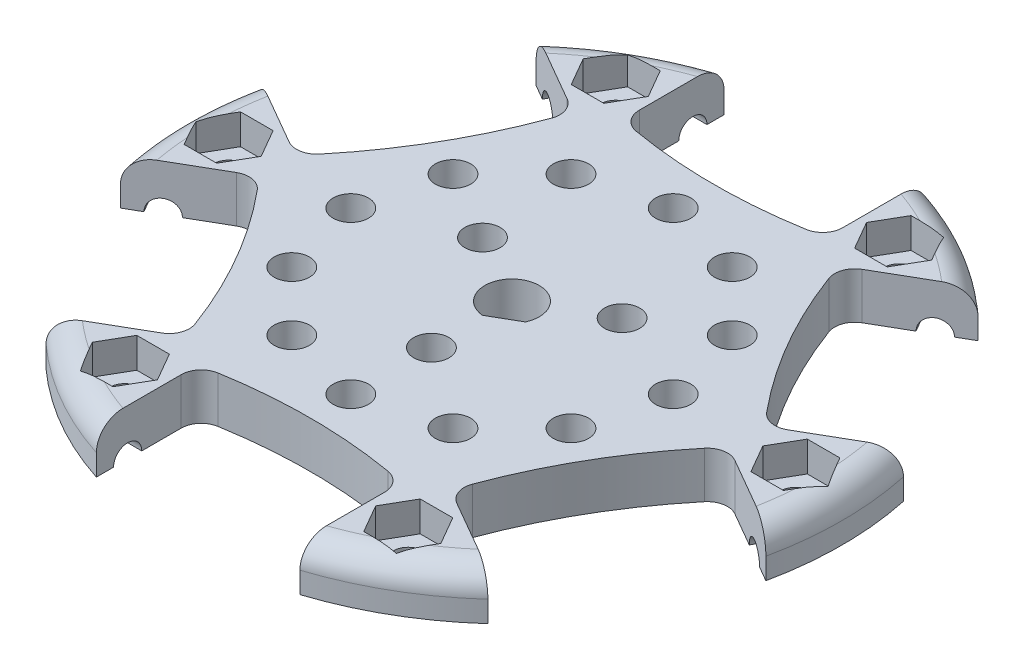
SolidWorks part; units mm, degrees
ref_plane "Plano frontal" through (0, 0, 0) normal (0, 0, 1) x (1, 0, 0)
ref_plane "Plano superior" through (0, 0, 0) normal (0, 1, 0) x (1, 0, 0)
ref_plane "Plano direito" through (0, 0, 0) normal (1, 0, 0) x (0, 0, -1)
sketch "Esboço1" plane through (0, 0, 0) normal (0, 0, 1) x (1, 0, 0)
  line L1 (-32.75, 2.1) -> (-32.75, 0)
  line L2 (-30.25, 4.6) -> (-6.07, 4.6)
  line L15 (-6.07, 4.6) -> (0, 4.6)
  line L17 (0, 0) -> (0, 4.6)
  line L18 (-32.75, 0) -> (0, 0)
  arc A3 (-30.25, 4.6) -> (-32.75, 2.1) centre (-30.25, 2.1) ccw
revolve "Revolução3" add sketch "Esboço1" angle 360 about L17
sketch "Esboço3" plane through (0, 0, 0) normal (0, -1, 0) x (1, 0, 0)
  line L2 (-10.1, 71.55) -> (10.1, 71.55)
  line L3 (-10.1, 71.55) -> (-10.1, 22.7384)
  line L4 (10.1, 71.55) -> (10.1, 22.7384)
  line L5 (10.1, -71.55) -> (-10.1, -71.55)
  line L6 (10.1, -71.55) -> (10.1, -22.7384)
  line L7 (-10.1, -71.55) -> (-10.1, -22.7384)
  line L10 (56.9141, 44.5219) -> (67.0141, 27.0281)
  line L11 (56.9141, 44.5219) -> (14.642, 20.116)
  line L12 (67.0141, 27.0281) -> (24.742, 2.6223)
  line L13 (-56.9141, -44.5219) -> (-67.0141, -27.0281)
  line L14 (-56.9141, -44.5219) -> (-14.642, -20.116)
  line L15 (-67.0141, -27.0281) -> (-24.742, -2.6223)
  line L18 (-67.0141, 27.0281) -> (-56.9141, 44.5219)
  line L19 (-67.0141, 27.0281) -> (-24.742, 2.6223)
  line L20 (-56.9141, 44.5219) -> (-14.642, 20.116)
  line L21 (67.0141, -27.0281) -> (56.9141, -44.5219)
  line L22 (67.0141, -27.0281) -> (24.742, -2.6223)
  line L23 (56.9141, -44.5219) -> (14.642, -20.116)
  arc A1 (-8.4375, 20.7671) -> (8.4375, 20.7671) centre (0, 70.05) ccw
  arc A2 (8.4375, 20.7671) -> (10.1, 22.7384) centre (8.1, 22.7384) ccw
  arc A3 (-8.4375, 20.7671) -> (-10.1, 22.7384) centre (-8.1, 22.7384) cw
  arc A4 (8.4375, -20.7671) -> (-8.4375, -20.7671) centre (0, -70.05) ccw
  arc A5 (-8.4375, -20.7671) -> (-10.1, -22.7384) centre (-8.1, -22.7384) ccw
  arc A6 (8.4375, -20.7671) -> (10.1, -22.7384) centre (8.1, -22.7384) cw
  arc A7 (13.766, 17.6906) -> (22.2035, 3.0764) centre (60.6651, 35.025) ccw
  arc A8 (22.2035, 3.0764) -> (24.742, 2.6223) centre (23.742, 4.3544) ccw
  arc A9 (13.766, 17.6906) -> (14.642, 20.116) centre (15.642, 18.384) cw
  arc A10 (-13.766, -17.6906) -> (-22.2035, -3.0764) centre (-60.6651, -35.025) ccw
  arc A11 (-22.2035, -3.0764) -> (-24.742, -2.6223) centre (-23.742, -4.3544) ccw
  arc A12 (-13.766, -17.6906) -> (-14.642, -20.116) centre (-15.642, -18.384) cw
  arc A13 (-22.2035, 3.0764) -> (-13.766, 17.6906) centre (-60.6651, 35.025) ccw
  arc A14 (-13.766, 17.6906) -> (-14.642, 20.116) centre (-15.642, 18.384) ccw
  arc A15 (-22.2035, 3.0764) -> (-24.742, 2.6223) centre (-23.742, 4.3544) cw
  arc A16 (22.2035, -3.0764) -> (13.766, -17.6906) centre (60.6651, -35.025) ccw
  arc A17 (13.766, -17.6906) -> (14.642, -20.116) centre (15.642, -18.384) ccw
  arc A18 (22.2035, -3.0764) -> (24.742, -2.6223) centre (23.742, -4.3544) cw
extrude "Corte-extrusão2" cut sketch "Esboço3" against normal blind 10
sketch "Esboço5" plane through (0, 0, 0) normal (0, -1, 0) x (1, 0, 0)
  line L0 (-12.6, 26.65) -> (12.6, 26.65)
  line L1 (-12.6, 28.05) -> (12.6, 28.05)
  line L10 (-12.6, 28.05) -> (-12.6, 26.65)
  line L13 (12.6, 28.05) -> (12.6, 26.65)
revolve "Corte-Revolução3" cut sketch "Esboço5" angle 360 about L1
sketch "Esboço6" plane through (0, 0, 0) normal (0, -1, 0) x (1, 0, 0)
  line L21 (-29.3796, 2.4131) -> (-16.7796, 24.2369)
  line L22 (-30.592, 3.1131) -> (-17.992, 24.9369)
  line L23 (-30.592, 3.1131) -> (-29.3796, 2.4131)
  line L24 (-17.992, 24.9369) -> (-16.7796, 24.2369)
revolve "Corte-Revolução4" cut sketch "Esboço6" angle 360 about L22
sketch "Esboço7" plane through (0, 0, 0) normal (0, -1, 0) x (1, 0, 0)
  line L9 (-16.7796, -24.2369) -> (-29.3796, -2.4131)
  line L10 (-17.992, -24.9369) -> (-30.592, -3.1131)
  line L11 (-17.992, -24.9369) -> (-16.7796, -24.2369)
  line L12 (-30.592, -3.1131) -> (-29.3796, -2.4131)
revolve "Corte-Revolução5" cut sketch "Esboço7" angle 360 about L10
sketch "Esboço8" plane through (0, 0, 0) normal (0, -1, 0) x (1, 0, 0)
  line L13 (16.7796, 24.2369) -> (29.3796, 2.4131)
  line L14 (17.992, 24.9369) -> (30.592, 3.1131)
  line L15 (17.992, 24.9369) -> (16.7796, 24.2369)
  line L16 (30.592, 3.1131) -> (29.3796, 2.4131)
revolve "Corte-Revolução6" cut sketch "Esboço8" angle 360 about L14
sketch "Esboço10" plane through (0, 0, 0) normal (0, -1, 0) x (1, 0, 0)
  line L1 (12.6, -26.65) -> (-12.6, -26.65)
  line L2 (12.6, -28.05) -> (-12.6, -28.05)
  line L3 (12.6, -28.05) -> (12.6, -26.65)
  line L4 (-12.6, -28.05) -> (-12.6, -26.65)
revolve "Corte-Revolução7" cut sketch "Esboço10" angle 360 about L2
sketch "Esboço11" plane through (0, 0, 0) normal (0, -1, 0) x (1, 0, 0)
  line L5 (29.3796, -2.4131) -> (16.7796, -24.2369)
  line L6 (30.592, -3.1131) -> (17.992, -24.9369)
  line L7 (30.592, -3.1131) -> (29.3796, -2.4131)
  line L8 (17.992, -24.9369) -> (16.7796, -24.2369)
revolve "Corte-Revolução8" cut sketch "Esboço11" angle 360 about L6
sketch "Esboço12" plane through (0, 0, 0) normal (0, -1, 0) x (1, 0, 0)
  circle A1 centre (0, 16) radius 1.75
  circle A2 centre (-8, 13.8564) radius 1.75
  circle A3 centre (-13.8564, 8) radius 1.75
  circle A4 centre (-16, 0) radius 1.75
  circle A5 centre (-13.8564, -8) radius 1.75
  circle A6 centre (-8, -13.8564) radius 1.75
  circle A7 centre (0, -16) radius 1.75
  circle A8 centre (8, -13.8564) radius 1.75
  circle A9 centre (13.8564, -8) radius 1.75
  circle A10 centre (16, 0) radius 1.75
  circle A11 centre (13.8564, 8) radius 1.75
  circle A12 centre (8, 13.8564) radius 1.75
  circle A13 centre (28.1296, 0) radius 1.3
  circle A14 centre (14.0648, 24.3609) radius 1.3
  circle A15 centre (-14.0648, 24.3609) radius 1.3
  circle A16 centre (-28.1296, 0) radius 1.3
  circle A18 centre (14.0648, -24.3609) radius 1.3
  circle A19 centre (-14.0648, -24.3609) radius 1.3
  circle A22 centre (0, 8) radius 1.75
  circle A23 centre (-6.9282, -4) radius 1.75
  circle A24 centre (6.9282, -4) radius 1.75
extrude "Corte-extrusão4" cut sketch "Esboço12" against normal through all
sketch "Esboço14" plane through (0, 4.6, 0) normal (0, 1, 0) x (1, 0, 0)
  line L1 (-31.0163, 0) -> (-29.573, -2.5)
  line L2 (-29.573, -2.5) -> (-26.6862, -2.5)
  line L3 (-26.6862, -2.5) -> (-25.2428, 0)
  line L4 (-25.2428, 0) -> (-26.6862, 2.5)
  line L5 (-26.6862, 2.5) -> (-29.573, 2.5)
  line L6 (-29.573, 2.5) -> (-31.0163, 0)
  line L8 (-15.5082, 26.8609) -> (-16.9515, 24.3609)
  line L9 (-16.9515, 24.3609) -> (-15.5082, 21.8609)
  line L10 (-15.5082, 21.8609) -> (-12.6214, 21.8609)
  line L11 (-12.6214, 21.8609) -> (-11.178, 24.3609)
  line L12 (-11.178, 24.3609) -> (-12.6214, 26.8609)
  line L13 (-12.6214, 26.8609) -> (-15.5082, 26.8609)
  line L15 (15.5082, 26.8609) -> (12.6214, 26.8609)
  line L16 (12.6214, 26.8609) -> (11.178, 24.3609)
  line L17 (11.178, 24.3609) -> (12.6214, 21.8609)
  line L18 (12.6214, 21.8609) -> (15.5082, 21.8609)
  line L19 (15.5082, 21.8609) -> (16.9515, 24.3609)
  line L20 (16.9515, 24.3609) -> (15.5082, 26.8609)
  line L22 (31.0163, 0) -> (29.573, 2.5)
  line L23 (29.573, 2.5) -> (26.6862, 2.5)
  line L24 (26.6862, 2.5) -> (25.2428, 0)
  line L25 (25.2428, 0) -> (26.6862, -2.5)
  line L26 (26.6862, -2.5) -> (29.573, -2.5)
  line L27 (29.573, -2.5) -> (31.0163, 0)
  line L29 (15.5082, -26.8609) -> (16.9515, -24.3609)
  line L30 (16.9515, -24.3609) -> (15.5082, -21.8609)
  line L31 (15.5082, -21.8609) -> (12.6214, -21.8609)
  line L32 (12.6214, -21.8609) -> (11.178, -24.3609)
  line L33 (11.178, -24.3609) -> (12.6214, -26.8609)
  line L34 (12.6214, -26.8609) -> (15.5082, -26.8609)
  line L36 (-15.5082, -26.8609) -> (-12.6214, -26.8609)
  line L37 (-12.6214, -26.8609) -> (-11.178, -24.3609)
  line L38 (-11.178, -24.3609) -> (-12.6214, -21.8609)
  line L39 (-12.6214, -21.8609) -> (-15.5082, -21.8609)
  line L40 (-15.5082, -21.8609) -> (-16.9515, -24.3609)
  line L41 (-16.9515, -24.3609) -> (-15.5082, -26.8609)
  circle A0 centre (-28.1296, 0) radius 2.5 construction
  circle A1 centre (-14.0648, 24.3609) radius 2.5 construction
  circle A2 centre (14.0648, 24.3609) radius 2.5 construction
  circle A3 centre (28.1296, 0) radius 2.5 construction
  circle A4 centre (14.0648, -24.3609) radius 2.5 construction
  circle A5 centre (-14.0648, -24.3609) radius 2.5 construction
extrude "Corte-extrusão6" cut sketch "Esboço14" against normal blind 3
sketch "Esboço13" plane through (0, 0, 0) normal (0, -1, 0) x (1, 0, 0)
  line L2 (2.3776, 1.0522) -> (-0.2776, 2.5851)
  arc A0 (-0.2776, 2.5851) -> (2.3776, 1.0522) centre (0, 0) ccw
extrude "Corte-extrusão7" cut sketch "Esboço13" against normal blind 10
sketch "Esboço16" plane through (0, 4.6, 0) normal (0, 1, 0) x (1, 0, 0)
  circle A0 centre (14.0648, 24.3609) radius 1.5
  circle A1 centre (28.1296, 0) radius 1.5
  circle A2 centre (14.0648, -24.3609) radius 1.5
  circle A3 centre (-14.0648, -24.3609) radius 1.5
  circle A4 centre (-28.1296, 0) radius 1.5
  circle A5 centre (-14.0648, 24.3609) radius 1.5
extrude "Corte-extrusão8" cut sketch "Esboço16" against normal through all
sketch "Esboço17" plane through (0, 4.6, 0) normal (0, 1, 0) x (1, 0, 0)
  line L0 (12.4482, -21.5609) -> (10.8316, -24.3609)
  line L1 (-29.7462, 2.8) -> (-31.3627, 0)
  line L2 (-31.3627, 0) -> (-29.7462, -2.8)
  line L3 (-29.7462, -2.8) -> (-26.513, -2.8)
  line L4 (-26.513, -2.8) -> (-24.8964, 0)
  line L5 (-24.8964, 0) -> (-26.513, 2.8)
  line L6 (-26.513, 2.8) -> (-29.7462, 2.8)
  line L7 (10.8316, -24.3609) -> (12.4482, -27.1609)
  line L8 (12.4482, -27.1609) -> (15.6814, -27.1609)
  line L9 (15.6814, -27.1609) -> (17.298, -24.3609)
  line L10 (17.298, -24.3609) -> (15.6814, -21.5609)
  line L11 (15.6814, -21.5609) -> (12.4482, -21.5609)
  line L12 (-15.6814, 27.1609) -> (-17.298, 24.3609)
  line L13 (-17.298, 24.3609) -> (-15.6814, 21.5609)
  line L14 (-10.8316, 24.3609) -> (-12.4482, 27.1609)
  line L15 (-12.4482, 21.5609) -> (-10.8316, 24.3609)
  line L16 (-15.6814, 21.5609) -> (-12.4482, 21.5609)
  line L17 (-12.4482, 27.1609) -> (-15.6814, 27.1609)
  line L18 (-17.298, -24.3609) -> (-15.6814, -27.1609)
  line L19 (-12.4482, -27.1609) -> (-10.8316, -24.3609)
  line L20 (-10.8316, -24.3609) -> (-12.4482, -21.5609)
  line L21 (-15.6814, -21.5609) -> (-17.298, -24.3609)
  line L22 (-15.6814, -27.1609) -> (-12.4482, -27.1609)
  line L23 (-12.4482, -21.5609) -> (-15.6814, -21.5609)
  line L24 (12.4482, 27.1609) -> (10.8316, 24.3609)
  line L25 (17.298, 24.3609) -> (15.6814, 27.1609)
  line L26 (12.4482, 21.5609) -> (15.6814, 21.5609)
  line L27 (15.6814, 21.5609) -> (17.298, 24.3609)
  line L28 (15.6814, 27.1609) -> (12.4482, 27.1609)
  line L29 (10.8316, 24.3609) -> (12.4482, 21.5609)
  line L30 (29.7462, -2.8) -> (31.3627, 0)
  line L31 (26.513, -2.8) -> (29.7462, -2.8)
  line L32 (24.8964, 0) -> (26.513, -2.8)
  line L33 (31.3627, 0) -> (29.7462, 2.8)
  line L34 (29.7462, 2.8) -> (26.513, 2.8)
  line L35 (26.513, 2.8) -> (24.8964, 0)
  circle A0 centre (-28.1296, 0) radius 2.8 construction
  circle A1 centre (14.0648, -24.3609) radius 2.8 construction
  circle A2 centre (-14.0648, 24.3609) radius 2.8 construction
  circle A3 centre (-14.0648, -24.3609) radius 2.8 construction
  circle A4 centre (14.0648, 24.3609) radius 2.8 construction
  circle A5 centre (28.1296, 0) radius 2.8 construction
extrude "Corte-extrusão9" cut sketch "Esboço17" against normal blind 3
sketch "Esboço18" plane through (0, 4.6, 0) normal (0, 1, 0) x (1, 0, 0)
  line L0 (-0.2555, -2.6879) -> (2.4555, -1.1226)
  arc A0 (2.4555, -1.1226) -> (-0.2555, -2.6879) centre (0, 0) ccw
extrude "Corte-extrusão10" cut sketch "Esboço18" against normal through all
